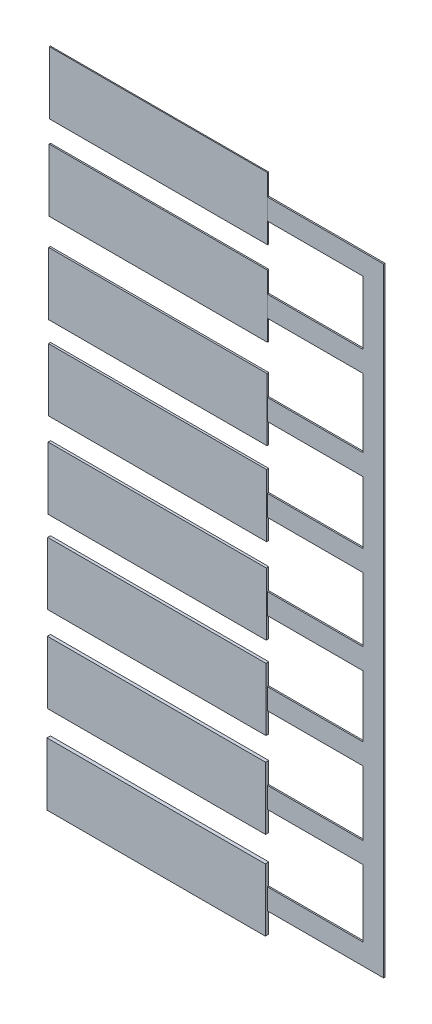
SolidWorks part; units mm, degrees
ref_plane "Plano frontal" through (0, 0, 0) normal (0, 0, 1) x (1, 0, 0)
ref_plane "Plano superior" through (0, 0, 0) normal (0, 1, 0) x (1, 0, 0)
ref_plane "Plano direito" through (0, 0, 0) normal (1, 0, 0) x (0, 0, -1)
sketch "Esboço9" plane through (0, 0, 0) normal (0, 0, 1) x (1, 0, 0)
  line L9 (70.4484, 443.2352) -> (7.6589, 443.2352)
  line L10 (7.6589, 443.2352) -> (7.6589, 425.2352)
  line L11 (7.6589, 425.2352) -> (70.4484, 425.2352)
  line L12 (70.4484, 425.2352) -> (70.4484, 443.2352)
extrude "Ressalto-extrusão9" add sketch "Esboço9" along normal blind 0.3 separate body
sketch "Esboço8" plane through (0, 0, 0) normal (0, 0, 1) x (1, 0, 0)
  line L0 (7.6589, 419.0171) -> (7.6589, 401.0171)
  line L5 (7.6589, 401.0171) -> (70.4484, 401.0171)
  line L6 (70.4484, 401.0171) -> (70.4484, 419.0171)
  line L7 (70.4484, 419.0171) -> (7.6589, 419.0171)
extrude "Ressalto-extrusão8" add sketch "Esboço8" along normal blind 0.4 separate body
sketch "Esboço1" plane through (0, 0, 0) normal (0, 0, 1) x (1, 0, 0)
  line L1 (7.6589, 393.2868) -> (70.4484, 393.2868)
  line L2 (7.6589, 393.2868) -> (7.6589, 375.2868)
  line L3 (7.6589, 375.2868) -> (70.4484, 375.2868)
  line L4 (70.4484, 393.2868) -> (70.4484, 375.2868)
extrude "Ressalto-extrusão1" add sketch "Esboço1" along normal blind 0.5 contours L1 L4 L3 L2
sketch "Esboço2" plane through (0, 0, 0) normal (0, 0, -1) x (-1, 0, 0)
  line L0 (-70.4484, 369.4042) -> (-7.6589, 369.4042)
  line L5 (-70.4484, 369.4042) -> (-70.4484, 351.4042)
  line L6 (-70.4484, 351.4042) -> (-7.6589, 351.4042)
  line L7 (-7.6589, 369.4042) -> (-7.6589, 351.4042)
extrude "Ressalto-extrusão2" add sketch "Esboço2" against normal blind 0.6 separate body
sketch "Esboço3" plane through (0, 0, 0) normal (0, 0, 1) x (1, 0, 0)
  line L0 (70.4484, 326.9341) -> (70.4484, 344.9341)
  line L5 (70.4484, 344.9341) -> (7.6589, 344.9341)
  line L6 (7.6589, 344.9341) -> (7.6589, 326.9341)
  line L7 (7.6589, 326.9341) -> (70.4484, 326.9341)
extrude "Ressalto-extrusão3" add sketch "Esboço3" along normal blind 0.7 separate body
sketch "Esboço4" plane through (0, 0, 0) normal (0, 0, 1) x (1, 0, 0)
  line L0 (7.6589, 303.2342) -> (70.4484, 303.2342)
  line L5 (70.4484, 303.2342) -> (70.4484, 321.2342)
  line L6 (70.4484, 321.2342) -> (7.6589, 321.2342)
  line L7 (7.6589, 321.2342) -> (7.6589, 303.2342)
extrude "Ressalto-extrusão4" add sketch "Esboço4" along normal blind 0.8 separate body
sketch "Esboço5" plane through (0, 0, 0) normal (0, 0, 1) x (1, 0, 0)
  line L0 (7.6589, 296.6485) -> (7.6589, 278.6485)
  line L5 (7.6589, 278.6485) -> (70.4484, 278.6485)
  line L6 (70.4484, 278.6485) -> (70.4484, 296.6485)
  line L7 (70.4484, 296.6485) -> (7.6589, 296.6485)
extrude "Ressalto-extrusão5" add sketch "Esboço5" along normal blind 0.9 separate body
sketch "Esboço6" plane through (0, 0, 0) normal (0, 0, 1) x (1, 0, 0)
  line L0 (70.4484, 271.3714) -> (7.6589, 271.3714)
  line L5 (7.6589, 271.3714) -> (7.6589, 253.3714)
  line L6 (7.6589, 253.3714) -> (70.4484, 253.3714)
  line L7 (70.4484, 253.3714) -> (70.4484, 271.3714)
extrude "Ressalto-extrusão6" add sketch "Esboço6" along normal blind 1 separate body
sketch "Esboço7" plane through (0, 0, 0) normal (0, 0, 1) x (1, 0, 0)
  line L0 (97.8995, 363.4042) -> (97.8995, 381.2868)
  line L1 (70.4484, 309.2342) -> (70.4484, 315.2342)
  line L3 (70.4484, 284.6485) -> (70.4484, 290.6485)
  line L6 (70.4484, 259.3714) -> (70.4484, 265.3714)
  line L7 (70.4484, 332.9341) -> (70.4484, 338.9341)
  line L8 (70.4484, 381.2868) -> (97.8995, 381.2868)
  line L9 (70.4484, 431.2352) -> (70.4484, 437.2352)
  line L10 (70.4484, 381.2868) -> (70.4484, 387.2868)
  line L11 (97.8995, 265.3714) -> (97.8995, 284.6485)
  line L13 (70.4484, 357.4042) -> (70.4484, 363.4042)
  line L14 (70.4484, 265.3714) -> (97.8995, 265.3714)
  line L15 (70.4484, 437.2352) -> (103.8995, 437.2352)
  line L17 (70.4484, 357.4042) -> (97.8995, 357.4042)
  line L18 (70.4484, 332.9341) -> (97.8995, 332.9341)
  line L19 (70.4484, 309.2342) -> (97.8995, 309.2342)
  line L20 (70.4484, 284.6485) -> (97.8995, 284.6485)
  line L21 (70.4484, 387.2868) -> (97.8995, 387.2868)
  line L22 (103.8995, 259.3714) -> (103.8995, 387.2868)
  line L23 (70.4484, 259.3714) -> (103.8995, 259.3714)
  line L24 (70.4484, 363.4042) -> (97.8995, 363.4042)
  line L25 (70.4484, 338.9341) -> (97.8995, 338.9341)
  line L26 (70.4484, 315.2342) -> (97.8995, 315.2342)
  line L27 (70.4484, 290.6485) -> (97.8995, 290.6485)
  line L29 (103.8995, 387.2868) -> (103.8995, 437.2352)
  line L30 (97.8995, 413.0171) -> (97.8995, 431.2352)
  line L31 (97.8995, 315.2342) -> (97.8995, 332.9341)
  line L32 (97.8995, 290.6485) -> (97.8995, 309.2342)
  line L33 (97.8995, 338.9341) -> (97.8995, 357.4042)
  line L34 (70.4484, 413.0171) -> (97.8995, 413.0171)
  line L35 (70.4484, 431.2352) -> (97.8995, 431.2352)
  line L36 (97.8995, 387.2868) -> (97.8995, 407.0171)
  line L37 (70.4484, 407.0171) -> (97.8995, 407.0171)
  line L38 (70.4484, 407.0171) -> (70.4484, 413.0171)
extrude "Ressalto-extrusão7" add sketch "Esboço7" along normal blind 0.4
